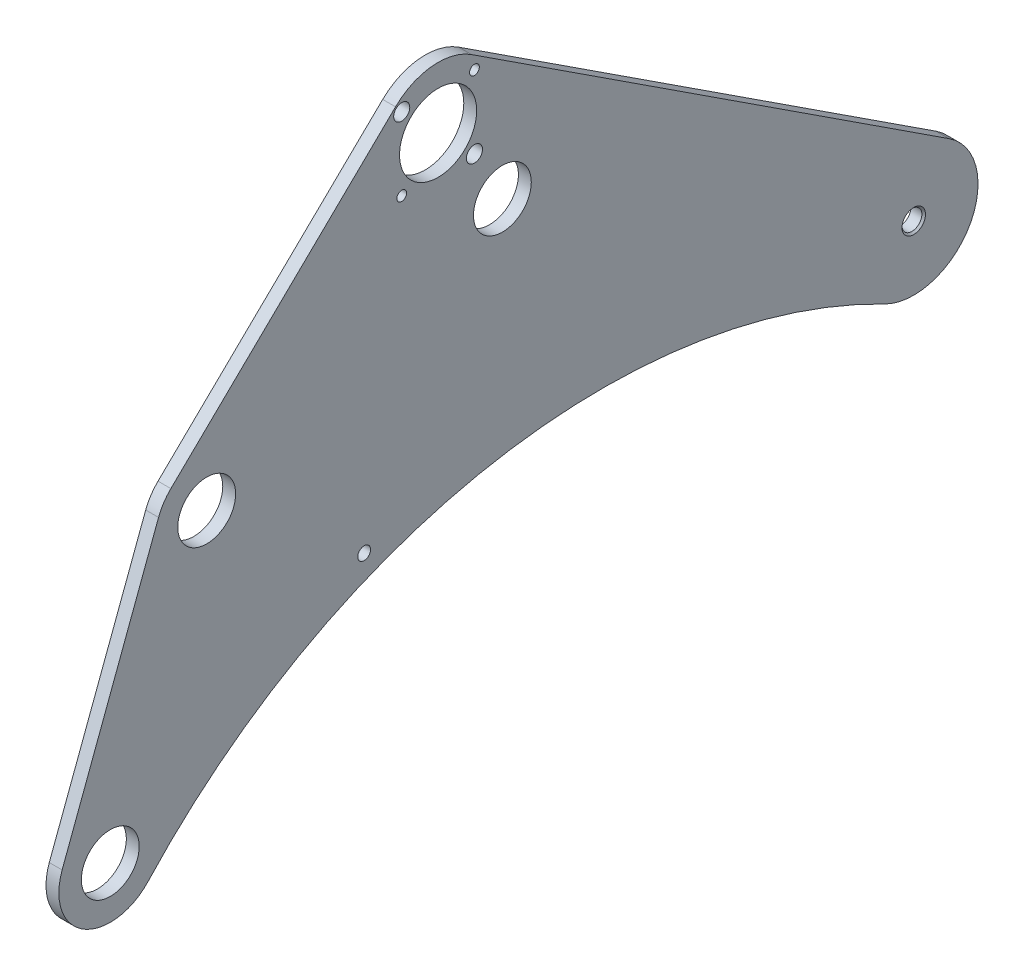
SolidWorks part; units mm, degrees
material "Acrylic (Medium-high impact)"
ref_plane "Front Plane" through (0, 0, 0) normal (0, 0, 1) x (1, 0, 0)
ref_plane "Top Plane" through (0, 0, 0) normal (0, 1, 0) x (1, 0, 0)
ref_plane "Right Plane" through (0, 0, 0) normal (1, 0, 0) x (0, 0, -1)
sketch "Sketch1" plane through (0, 0, 0) normal (1, 0, 0) x (0, 0, -1)
  line L0 (-548.7618, -304.8) -> (152.435, -304.8)
  line L1 (-192.8252, -101.6) -> (-152.4, -101.6)
  line L2 (-234.95, -143.7248) -> (-234.95, -186.4752)
  line L3 (-192.8252, -228.6) -> (-152.4, -228.6)
  line L4 (-152.4, -101.6) -> (-152.4, -228.6)
  circle A1 centre (0, 0) radius 6.35
  circle A6 centre (-396.875, -76.2) radius 9.525
  circle A7 centre (-349.25, 50.8) radius 9.525
  circle A8 centre (-203.2, 111.125) radius 9.525
  arc A9 (-234.95, -186.4752) -> (-192.8252, -228.6) centre (-192.8252, -186.4752) ccw
  arc A10 (-192.8252, -101.6) -> (-234.95, -143.7248) centre (-192.8252, -143.7248) ccw
  circle A11 centre (-192.8252, 12.7469) radius 120.65
  circle A12 centre (-234.95, 155.194) radius 29.845
  dimension "D1" = 12.7
  dimension "D2" = 19.05
  dimension "D3" = 42.1248
  dimension "D4" = 127
  dimension "D7" = 203.2
  dimension "D6" = 241.3
  dimension "D16" = 59.69
  dimension "D5" = 82.55
  dimension "D8" = 304.8
  dimension "D9" = 152.4
  dimension "D10" = 396.875
  dimension "D11" = 76.2
  dimension "D12" = 349.25
  dimension "D13" = 50.8
  dimension "D14" = 203.2
  dimension "D15" = 111.125
  dimension "D17" = 234.95
  dimension "D18" = 155.194
sketch "Sketch2" plane through (0, 0, 0) normal (1, 0, 0) x (0, 0, -1)
  line L1 (-420.6578, -67.2815) -> (-373.0328, 59.7185)
  line L3 (-366.9483, 69.0189) -> (-255.9667, 176.829)
  line L5 (-218.4679, 180.455) -> (17.3496, 26.5905)
  line L6 (-1001.8623, -101.6) -> (216.545, -101.6) construction
  line L7 (-1029.8132, 185.3565) -> (188.5941, 185.3565) construction
  arc A0 (-366.9483, 69.0189) -> (-373.0328, 59.7185) centre (-349.25, 50.8) ccw
  arc A2 (-420.6578, -67.2815) -> (-378.1608, -93.3738) centre (-396.875, -76.2) ccw
  arc A4 (-218.4679, 180.455) -> (-255.9667, 176.829) centre (-234.95, 155.194) ccw
  arc A5 (-14.4897, -28.2509) -> (17.3496, 26.5905) centre (0, 0) ccw
  arc A8 (-378.1608, -93.3738) -> (-14.4897, -28.2509) centre (-153.5905, -299.4593) cw
  circle A12 centre (-396.875, -76.2) radius 9.525 construction
  circle A13 centre (-349.25, 50.8) radius 9.525 construction
  dimension "D1" = 25.4
  dimension "D2" = 63.5
  dimension "D3" = 60.325
  dimension "D4" = 304.8
  dimension "D6" = 286.9565
extrude "Boss-Extrude1" add sketch "Sketch2" along normal blind 6.35
sketch "Sketch3" plane through (6.35, 0, 0) normal (1, 0, 0) x (0, 0, -1)
  line L0 (-216.9895, 173.1545) -> (-252.9105, 137.2335) construction
  line L1 (-234.95, 155.194) -> (-234.95, 205.0182) construction
  line L2 (-252.9105, 173.1545) -> (-216.9895, 137.2335) construction
  circle A0 centre (-203.2, 111.125) radius 14.2875
  circle A1 centre (-349.25, 50.8) radius 14.2875
  circle A2 centre (-396.875, -76.2) radius 14.2875
  circle A3 centre (-234.95, 155.194) radius 19.05
  circle A5 centre (-252.9105, 137.2335) radius 2.413
  circle A7 centre (-216.9895, 137.2335) radius 3.9687
  circle A8 centre (-216.9895, 173.1545) radius 2.413
  circle A9 centre (-252.9105, 173.1545) radius 3.9687
  point P18 (-234.95, 155.194)
  point P28 (-234.95, 155.194)
  dimension "D1" = 38.1
  dimension "D2" = 28.575
  dimension "D3" = 4.826
  dimension "D4" = 50.8
  dimension "D5" = 45
  dimension "D6" = 7.9375
  dimension "D7" = 50.8
extrude "Cut-Extrude1" cut sketch "Sketch3" against normal up to next
hole_wizard "3/8 Clearance Hole2" positions "Sketch7" profile "Sketch8" hole size "3/8" standard "ANSI Inch" end condition through all
sketch "Sketch7" plane through (6.35, 0, 0) normal (1, 0, 0) x (0, 0, -1)
  point P0 (0, 0)
sketch "Sketch8" plane through (6.35, 0, 0) normal (0, 1, 0) x (0, 0, -1)
  line L0 (0, 0) -> (0, 6.35)
  line L1 (0, 6.35) -> (4.9022, 6.35)
  line L2 (4.9022, 6.35) -> (4.9022, 0.8915)
  line L3 (4.9022, 0.8915) -> (5.7937, 0)
  line L5 (5.7937, 0) -> (0, 0)
  line L6 (-4.9022, 0.8915) -> (-5.7937, 0) construction
  line L11 (0, -6.35) -> (0, 107.95) construction
  dimension "Thru Hole Dia." = 9.8044
  dimension "Thru Hole Depth" = 6.35
  dimension "Near C'Sink Dia." = 11.5875
  dimension "Near C'Sink Angle" = 90
sketch "Sketch9" plane through (6.35, 0, 0) normal (1, 0, 0) x (0, 0, -1)
  line L0 (-495.9857, -101.6) -> (27.4607, -101.6) construction
  line L1 (100.4878, 185.3565) -> (-422.9585, 185.3565) construction
  arc A0 (-218.4679, 180.455) -> (-255.9667, 176.829) centre (-234.95, 155.194) ccw construction
  arc A1 (-420.6578, -67.2815) -> (-378.1608, -93.3738) centre (-396.875, -76.2) ccw construction
  dimension "D1" = 286.9565
hole_wizard "1/4 (0.2500) Dowel Hole2" positions "Sketch12" profile "Sketch13" hole size "1/4" standard "ANSI Inch" end condition through all
sketch "Sketch12" plane through (6.35, 0, 0) normal (1, 0, 0) x (0, 0, -1)
  point P0 (-271.4625, -6.35)
  point P6 (0, 0)
  point P7 (0, 0)
  point P8 (0, 0)
  dimension "D1" = 271.4625
sketch "Sketch13" plane through (6.35, -6.35, 271.4625) normal (0, 1, 0) x (0, 0, -1)
  line L0 (0, 0) -> (0, 6.35)
  line L1 (0, 6.35) -> (3.175, 6.35)
  line L2 (3.175, 6.35) -> (3.175, 0)
  line L5 (3.175, 0) -> (0, 0)
  line L11 (0, -6.35) -> (0, 107.95) construction
  dimension "Thru Hole Dia." = 6.35
  dimension "Thru Hole Depth" = 6.35
